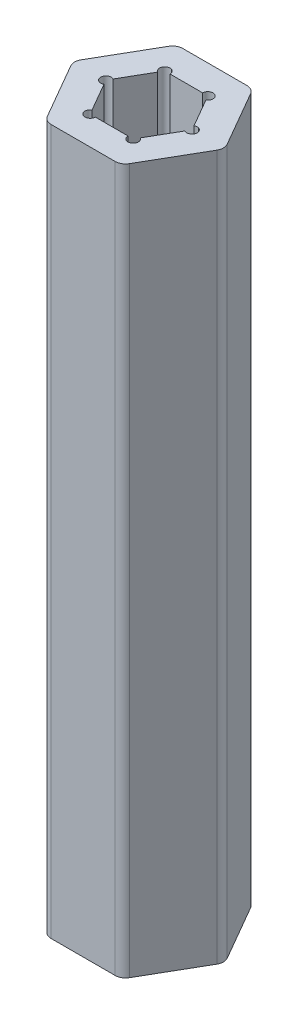
SolidWorks part; units mm, degrees
ref_plane "Front Plane" through (0, 0, 0) normal (0, 0, 1) x (1, 0, 0)
ref_plane "Top Plane" through (0, 0, 0) normal (0, 1, 0) x (1, 0, 0)
ref_plane "Right Plane" through (0, 0, 0) normal (1, 0, 0) x (0, 0, -1)
sketch "Sketch1" plane through (0, 0, 0) normal (0, 1, 0) x (1, 0, 0)
  line L1 (3.6662, 6.35) -> (-3.6662, 6.35)
  line L2 (-3.6662, 6.35) -> (-7.3323, 0)
  line L3 (-7.3323, 0) -> (-3.6662, -6.35)
  line L4 (-3.6662, -6.35) -> (3.6662, -6.35)
  line L5 (3.6662, -6.35) -> (7.3323, 0)
  line L6 (7.3323, 0) -> (3.6662, 6.35)
  line L7 (2.0785, 3.6) -> (-2.0785, 3.6)
  line L8 (-2.0785, 3.6) -> (-4.1569, 0)
  line L9 (-4.1569, 0) -> (-2.0785, -3.6)
  line L10 (-2.0785, -3.6) -> (2.0785, -3.6)
  line L11 (2.0785, -3.6) -> (4.1569, 0)
  line L12 (4.1569, 0) -> (2.0785, 3.6)
  circle A0 centre (0, 0) radius 6.35 construction
  circle A1 centre (0, 0) radius 3.6 construction
  point P10 (0, 0)
  dimension "D1" = 12.7
  dimension "D2" = 7.2
extrude "Boss-Extrude1" add sketch "Sketch1" along normal blind 68
sketch "Sketch2" plane through (0, 68, 0) normal (0, 1, 0) x (1, 0, 0)
  circle A0 centre (-2.0785, 3.6) radius 0.5
  circle A1 centre (2.0785, 3.6) radius 0.5
  circle A2 centre (4.1569, 0) radius 0.5
  circle A3 centre (2.0785, -3.6) radius 0.5
  circle A4 centre (-2.0785, -3.6) radius 0.5
  circle A5 centre (-4.1569, 0) radius 0.5
  dimension "D1" = 1
extrude "Cut-Extrude1" cut sketch "Sketch2" against normal through all
fillet "Fillet1" radius 1 6 edges at (7.3323, 34, 0) (-3.6662, 34, 6.35) (-7.3323, 34, 0) (-3.6662, 34, -6.35) (3.6662, 34, -6.35) (3.6662, 34, 6.35)
